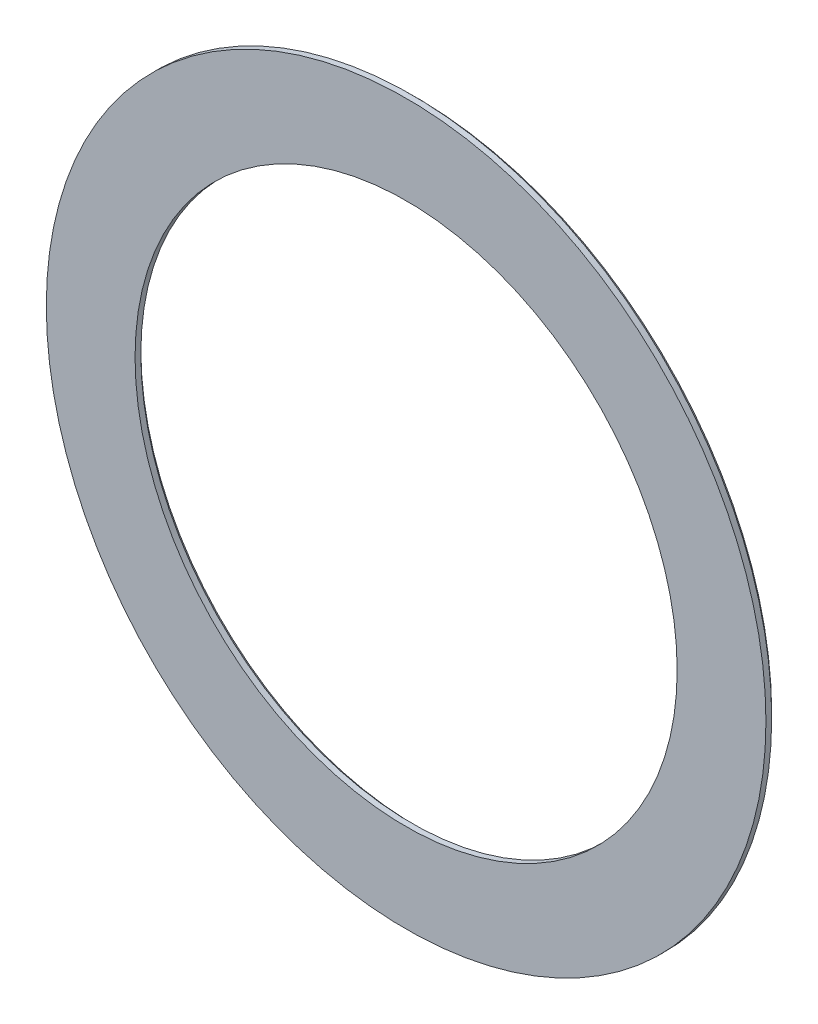
SolidWorks part; units mm, degrees
ref_plane "Front Plane" through (0, 0, 0) normal (1, 0, 0) x (0, 1, 0)
ref_plane "Top Plane" through (0, 0, 0) normal (0, 0, 1) x (0, 1, 0)
ref_plane "Right Plane" through (0, 0, 0) normal (0, 1, 0) x (-1, 0, 0)
sketch "Sketch1" plane through (0, 0, 0) normal (0, 0, 1) x (0, 1, 0)
  circle A0 centre (0, 0) radius 21.15
  circle A1 centre (0, 0) radius 28.075
  dimension "D1" = 42.3
  dimension "D2" = 56.15
extrude "Boss-Extrude1" add sketch "Sketch1" along normal blind 0.75
chamfer "Chamfer1" distance 0.3 angle 45 2 edges at (28.075, 0, 0) (21.15, 0, 0)
